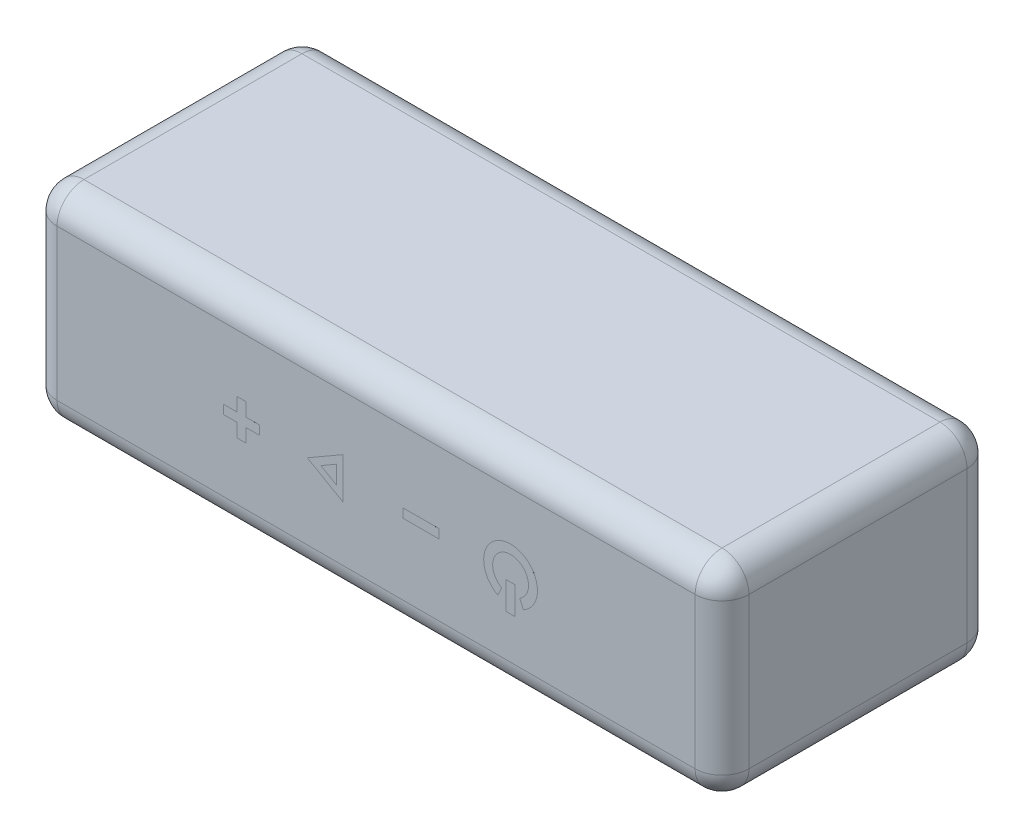
SolidWorks part; units mm, degrees
material "ABS"
ref_plane "Front Plane" through (0, 0, 0) normal (0, 0, 1) x (1, 0, 0)
ref_plane "Top Plane" through (0, 0, 0) normal (0, 1, 0) x (1, 0, 0)
ref_plane "Right Plane" through (0, 0, 0) normal (1, 0, 0) x (0, 0, -1)
sketch "Sketch1" plane through (0, 0, 0) normal (0, 1, 0) x (1, 0, 0)
  line L1 (0, 0) -> (196, 0)
  line L2 (0, 0) -> (0, 77)
  line L3 (0, 77) -> (196, 77)
  line L4 (196, 0) -> (196, 77)
  dimension "D1" = 196
  dimension "D2" = 77
extrude "Boss-Extrude1" add sketch "Sketch1" along normal blind 58
fillet "Fillet1" radius 7.62 12 edges at (0, 58, -38.5) (98, 58, -77) (0, 29, -77) (196, 58, -38.5) (196, 29, -77) (196, 0, -38.5) (98, 0, -77) (0, 0, -38.5) (0, 29, 0) (98, 58, 0) (196, 29, 0) (98, 0, 0)
sketch "Sketch2" plane through (0, 0, 0) normal (0, 0, 1) x (1, 0, 0)
  line L0 (188.38, 29) -> (7.62, 29) construction
  line L1 (188.38, 7.62) -> (188.38, 50.38) construction
  line L2 (7.62, 50.38) -> (7.62, 7.62) construction
  line L3 (139.699, 22.2835) -> (138.7063, 24.6396)
  line L4 (133.5595, 24.6009) -> (132.4899, 22.2894)
  line L5 (136.1, 29) -> (136.1, 14.8729) construction
  line L6 (137.37, 27.2789) -> (134.83, 27.2789)
  line L7 (137.37, 27.2789) -> (137.37, 19.4428)
  line L8 (137.37, 19.4428) -> (134.83, 19.4428)
  line L9 (134.83, 27.2789) -> (134.83, 19.4428)
  line L10 (86.7817, 26.4337) -> (86.7817, 31.5663)
  line L11 (115.78, 27.73) -> (105.62, 27.73)
  line L12 (115.78, 27.73) -> (115.78, 30.27)
  line L13 (115.78, 30.27) -> (105.62, 30.27)
  line L14 (105.62, 27.73) -> (105.62, 30.27)
  line L15 (86.7817, 31.5663) -> (82.3367, 29)
  line L16 (82.3367, 29) -> (86.7817, 26.4337)
  line L17 (88.6867, 23.1341) -> (83.6067, 31.9329) construction
  line L18 (78.5267, 29) -> (88.6867, 23.1341)
  line L19 (88.6867, 23.1341) -> (88.6867, 34.8659)
  line L20 (88.6867, 34.8659) -> (78.5267, 29)
  line L21 (110.7, 30.27) -> (110.7, 27.73) construction
  line L22 (64.98, 27.73) -> (54.82, 27.73)
  line L23 (64.98, 27.73) -> (64.98, 30.27)
  line L24 (64.98, 30.27) -> (54.82, 30.27)
  line L25 (54.82, 27.73) -> (54.82, 30.27)
  line L26 (59.9, 34.08) -> (59.9, 23.92) construction
  line L27 (61.17, 23.92) -> (58.63, 23.92)
  line L28 (61.17, 23.92) -> (61.17, 34.08)
  line L29 (61.17, 34.08) -> (58.63, 34.08)
  line L30 (58.63, 23.92) -> (58.63, 34.08)
  line L32 (98, 0) -> (98, 58) construction
  line L33 (188.38, 0) -> (7.62, 0) construction
  line L34 (7.62, 58) -> (188.38, 58) construction
  arc A0 (138.7063, 24.6396) -> (133.5595, 24.6009) centre (136.1, 29) ccw
  arc A1 (139.699, 22.2835) -> (132.4899, 22.2894) centre (136.1, 29) ccw
  point P15 (136.1, 27.2789)
  point P17 (105.62, 29)
  point P25 (54.82, 29)
  point P29 (85.3, 29)
  point P30 (88.6867, 29)
  point P42 (61.17, 29)
  point P45 (59.9, 27.73)
  point P46 (0, 0)
  point P47 (98, 0)
  dimension "D1" = 2.54
  dimension "D2" = 5.08
  dimension "D3" = 2.54
  dimension "D4" = 10.16
  dimension "D5" = 10.16
  dimension "D6" = 1.905
  dimension "D7" = 25.4
  dimension "D8" = 25.4
  dimension "D9" = 25.4
  dimension "D10" = 12.7
extrude "Boss-Extrude2" add sketch "Sketch2" along normal blind 0.001 contours L3 A1 L4 A0 | L6 L9 L8 L7 | L14 L11 L12 L13 | L19 L20 L18 L16 L15 L10 | L30 L24 L28 L29 | L28 L22 L23 L24 | L30 L22 L28 L24 | L30 L27 L28 L22 | L22 L30 L24 L25
